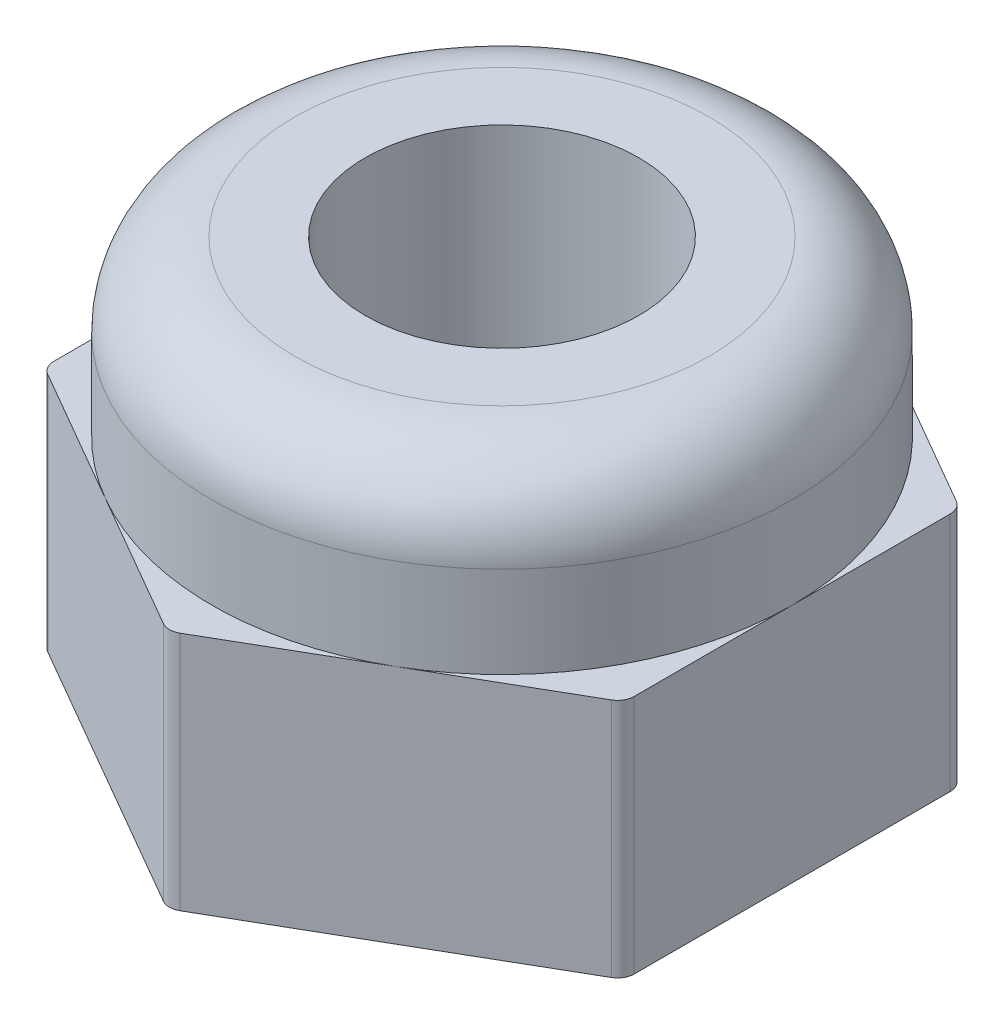
SolidWorks part; units mm, degrees
ref_plane "前视基准面" through (0, 0, 0) normal (0, 0, 1) x (1, 0, 0)
ref_plane "上视基准面" through (0, 0, 0) normal (0, 1, 0) x (1, 0, 0)
ref_plane "右视基准面" through (0, 0, 0) normal (1, 0, 0) x (0, 0, -1)
other "Configuration Table"
sketch "草图1" plane through (0, 0, 0) normal (0, 1, 0) x (1, 0, 0)
  line L1 (3.5, -2.0207) -> (3.5, 2.0207)
  line L2 (3.5, 2.0207) -> (0, 4.0415)
  line L3 (0, 4.0415) -> (-3.5, 2.0207)
  line L4 (-3.5, 2.0207) -> (-3.5, -2.0207)
  line L5 (-3.5, -2.0207) -> (0, -4.0415)
  line L6 (0, -4.0415) -> (3.5, -2.0207)
  circle A0 centre (0, 0) radius 3.5 construction
  dimension "D1" = 7
extrude "凸台-拉伸1" add sketch "草图1" along normal blind 2.9
sketch "草图2" plane through (0, 0, 0) normal (0, -1, 0) x (-1, 0, 0)
  circle A0 centre (0, 0) radius 3.5
extrude "凸台-拉伸2" add sketch "草图2" against normal blind 5
fillet "圆角2" radius 1 1 edges at (0, 5, -3.5)
fillet "圆角3" radius 0.2 6 edges at (-3.5, 1.45, -2.0207) (0, 1.45, -4.0415) (3.5, 1.45, -2.0207) (3.5, 1.45, 2.0207) (0, 1.45, 4.0415) (-3.5, 1.45, 2.0207)
sketch "草图4" plane through (0, 0, 0) normal (0, -1, 0) x (-1, 0, 0)
  point P0 (0, 0)
hole_wizard "M4 螺纹孔1" positions "草图4" profile "草图5" tap size "M4" standard "GB"
sketch "草图5" plane through (0, 0, 0) normal (1, 0, 0) x (0, 0, -1)
  line L0 (0, 0) -> (0, 11.0914)
  line L1 (0, 11.0914) -> (1.65, 10.1)
  line L2 (1.65, 10.1) -> (1.65, 0)
  line L5 (1.65, 0) -> (0, 0)
  line L10 (0, 11.0914) -> (-1.65, 10.1) construction
  line L11 (0, -6.35) -> (0, 107.95) construction
  dimension "螺纹孔钻头直径" = 3.3
  dimension "螺纹孔钻头深度" = 10.1
  dimension "导头角度" = 118
cosmetic thread "孔螺蚊线1" parameters "D1"=8, "D2"=4
